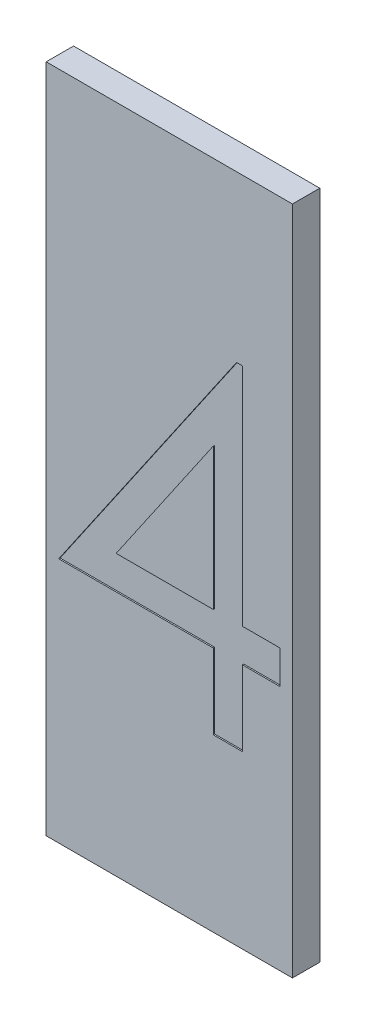
SolidWorks part; units mm, degrees
ref_plane "正面" through (0, 0, 0) normal (0, 0, 1) x (1, 0, 0)
ref_plane "平面" through (0, 0, 0) normal (0, 1, 0) x (1, 0, 0)
ref_plane "右側面" through (0, 0, 0) normal (1, 0, 0) x (0, 0, -1)
sketch "ｽｹｯﾁ1" plane through (0, 0, 0) normal (0, 0, 1) x (1, 0, 0)
  line L0 (18, 0) -> (0, 0)
  line L1 (18, 49) -> (0, 49)
  line L2 (0, 0) -> (0, 49)
  line L4 (18, 0) -> (18, 49)
extrude "ﾎﾞｽ - 押し出し1" add sketch "ｽｹｯﾁ1" along normal blind 2
sketch "ｽｹｯﾁ2" plane through (0, 0, 2) normal (0, 0, 1) x (1, 0, 0)
  text T0 "4" font "Century Gothic" height in points 90
extrude "ｶｯﾄ - 押し出し1" cut sketch "ｽｹｯﾁ2" against normal blind 0.1
